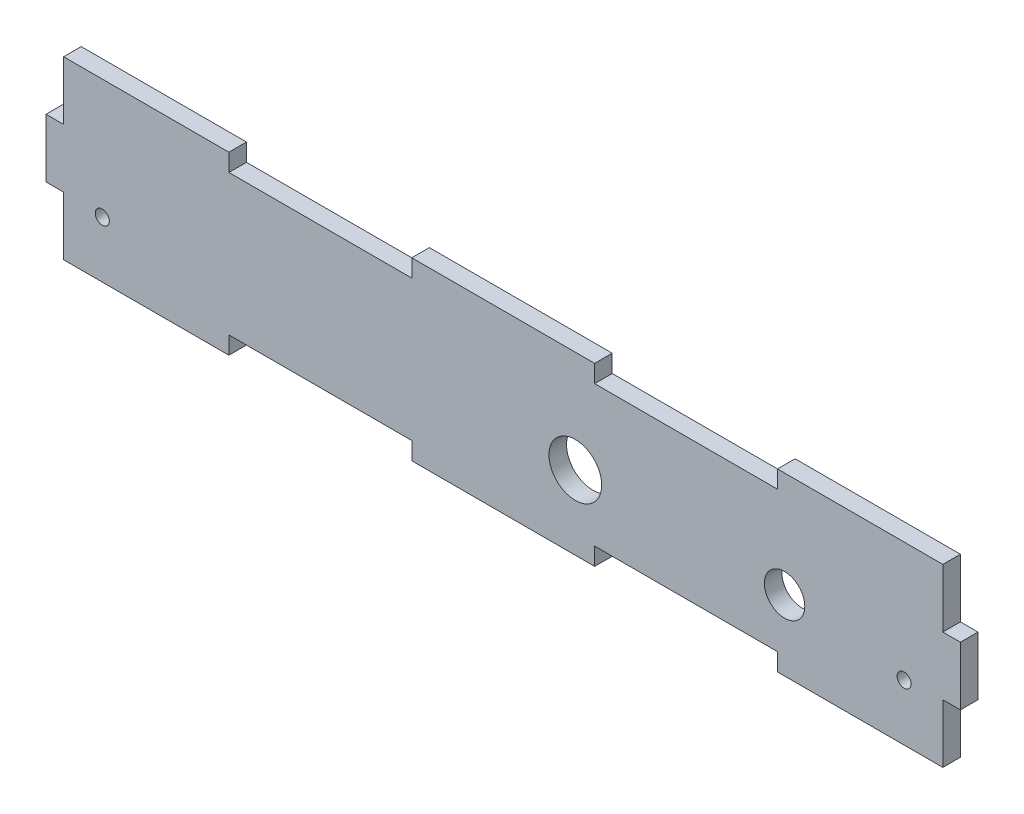
SolidWorks part; units mm, degrees
ref_plane "Alzado" through (0, 0, 0) normal (0, 0, 1) x (1, 0, 0)
ref_plane "Planta" through (0, 0, 0) normal (0, 1, 0) x (1, 0, 0)
ref_plane "Vista lateral" through (0, 0, 0) normal (1, 0, 0) x (0, 0, -1)
sketch "Croquis1" plane through (0, 0, 0) normal (0, 0, 1) x (1, 0, 0)
  line L0 (0, 33.3333) -> (5, 33.3333)
  line L1 (5, 0) -> (52, 0)
  line L2 (0, 16.6667) -> (0, 33.3333)
  line L3 (5, 50) -> (52, 50)
  line L4 (260, 16.6667) -> (260, 33.3333)
  line L5 (5, 33.3333) -> (5, 16.6667) construction
  line L6 (5, 16.6667) -> (0, 16.6667)
  line L7 (130, 50) -> (130, 31.9566) construction
  line L8 (0, 25) -> (30.953, 25) construction
  line L9 (5, 33.3333) -> (5, 50)
  line L10 (5, 16.6667) -> (5, 0)
  line L11 (0, 0) -> (5, 0) construction
  line L12 (0, 0) -> (0, 16.6667) construction
  line L13 (255, 16.6667) -> (255, 0)
  line L14 (255, 16.6667) -> (260, 16.6667)
  line L15 (260, 33.3333) -> (255, 33.3333)
  line L16 (255, 33.3333) -> (255, 50)
  line L17 (52, 0) -> (52, 5)
  line L18 (52, 5) -> (104, 5)
  line L19 (104, 5) -> (104, 0)
  line L20 (156, 5) -> (156, 0)
  line L21 (208, 5) -> (156, 5)
  line L22 (208, 0) -> (208, 5)
  line L23 (208, 50) -> (208, 45)
  line L24 (208, 45) -> (156, 45)
  line L25 (156, 45) -> (156, 50)
  line L26 (104, 45) -> (104, 50)
  line L27 (52, 45) -> (104, 45)
  line L28 (52, 50) -> (52, 45)
  line L29 (104, 50) -> (156, 50)
  line L30 (208, 50) -> (255, 50)
  line L31 (104, 0) -> (156, 0)
  line L32 (208, 0) -> (255, 0)
  circle A0 centre (16, 16) radius 2
  circle A1 centre (244, 16) radius 2
  dimension "D3" = 4
  dimension "D1" = 260
  dimension "D2" = 50
  dimension "D4" = 16.6667
  dimension "D5" = 5
  dimension "D6" = 52
  dimension "D7" = 52
  dimension "D8" = 5
  dimension "D9" = 16
  dimension "D10" = 16
extrude "Saliente-Extruir1" add sketch "Croquis1" along normal blind 5
sketch "Croquis2" plane through (0, 0, 5) normal (0, 0, 1) x (1, 0, 0)
  line L0 (156, 5) -> (208, 5) construction
  line L1 (52, 5) -> (104, 5) construction
  line L2 (260, 16.6667) -> (260, 33.3333) construction
  line L3 (160, 27) -> (141, 27) construction
  line L4 (160, 27) -> (160, 15) construction
  line L5 (160, 15) -> (141, 15) construction
  line L6 (141, 27) -> (141, 15) construction
  line L7 (160, 21) -> (141, 21) construction
  line L8 (150.5, 27) -> (150.5, 15) construction
  circle A0 centre (210, 20) radius 5.75
  circle A1 centre (150.5, 21) radius 7.5
  dimension "D1" = 11.5
  dimension "D8" = 15
  dimension "D2" = 50
  dimension "D3" = 15
  dimension "D4" = 19
  dimension "D5" = 12
  dimension "D6" = 50
  dimension "D7" = 10
extrude "Cortar-Extruir1" cut sketch "Croquis2" against normal blind 10
